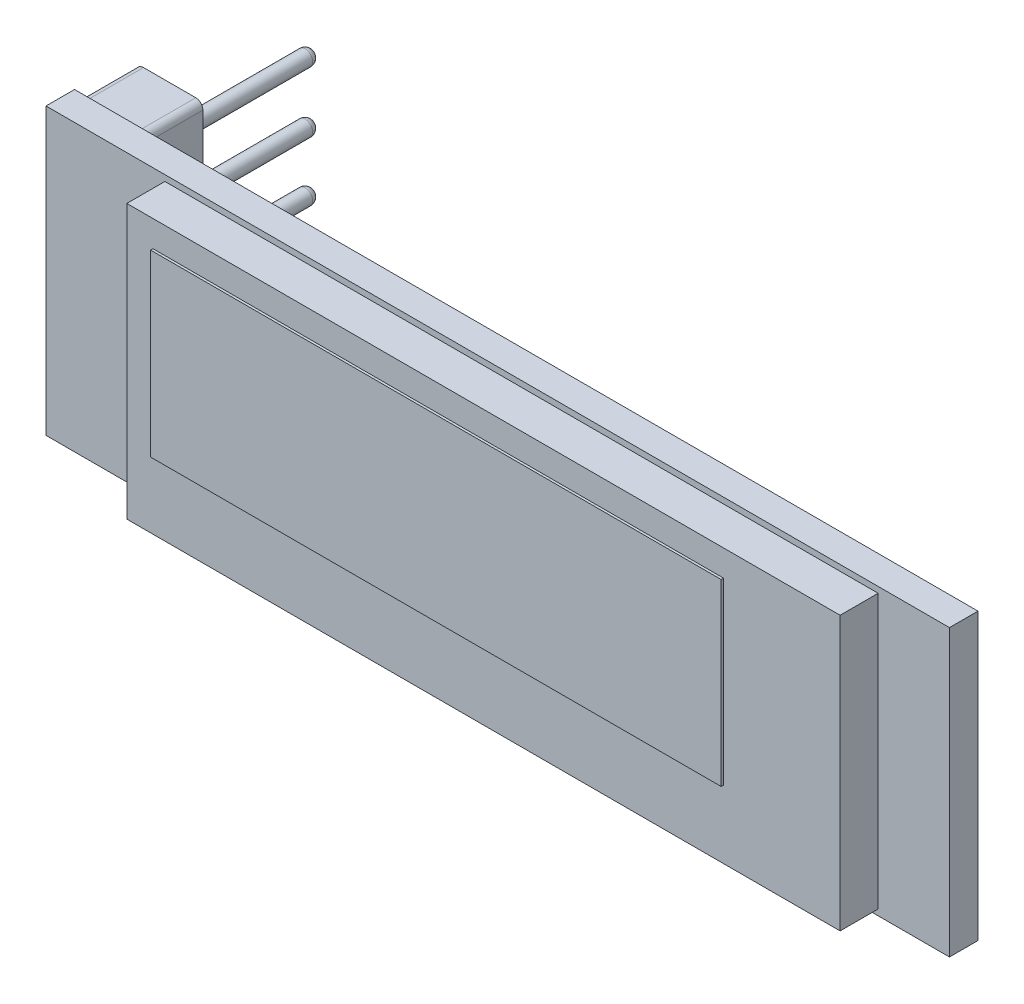
SolidWorks part; units mm, degrees
ref_plane "Front Plane" through (0, 0, 0) normal (0, 0, 1) x (1, 0, 0)
ref_plane "Top Plane" through (0, 0, 0) normal (0, 1, 0) x (1, 0, 0)
ref_plane "Right Plane" through (0, 0, 0) normal (1, 0, 0) x (0, 0, -1)
sketch "Sketch1" plane through (0, 0, 0) normal (0, 0, 1) x (1, 0, 0)
  line L1 (19, -6) -> (-19, -6)
  line L2 (19, -6) -> (19, 6)
  line L3 (19, 6) -> (-19, 6)
  line L4 (-19, -6) -> (-19, 6)
  line L5 (19, -6) -> (-19, 6) construction
  line L6 (19, 6) -> (-19, -6) construction
  point P0 (0, 0)
  dimension "D1" = 38
  dimension "D2" = 12
extrude "Boss-Extrude1" add sketch "Sketch1" along normal blind 1.2
sketch "Sketch2" plane through (0, 0, 1.2) normal (0, 0, 1) x (1, 0, 0)
  line L0 (-19, 6) -> (-19, -6) construction
  line L1 (-14, -5.75) -> (16, -5.75)
  line L2 (-14, -5.75) -> (-14, 5.75)
  line L3 (-14, 5.75) -> (16, 5.75)
  line L4 (16, -5.75) -> (16, 5.75)
  line L5 (-14, -5.75) -> (16, 5.75) construction
  line L6 (-14, 5.75) -> (16, -5.75) construction
  line L7 (-19, 0) -> (19, 0) construction
  line L8 (19, -6) -> (19, 6) construction
  point P0 (1, 0)
  dimension "D1" = 5
  dimension "D2" = 11.5
  dimension "D3" = 30
extrude "Boss-Extrude2" add sketch "Sketch2" along normal blind 1.6
sketch "Sketch4" plane through (0, 0, 2.8) normal (0, 0, 1) x (1, 0, 0)
  line L0 (-14, 0) -> (16, 0) construction
  line L1 (-14, 5.75) -> (-14, -5.75) construction
  line L2 (16, -5.75) -> (16, 5.75) construction
  line L3 (-19, 6) -> (-19, -6) construction
  line L4 (-12.9, 4.65) -> (11.1, 4.65)
  line L5 (-12.9, 4.65) -> (-12.9, -2.89)
  line L6 (-12.9, -2.89) -> (11.1, -2.89)
  line L7 (11.1, 4.65) -> (11.1, -2.89)
  line L8 (-12.9, 4.65) -> (11.1, -2.89) construction
  line L9 (-12.9, -2.89) -> (11.1, 4.65) construction
  line L10 (16, 5.75) -> (-14, 5.75) construction
  point P6 (-0.9, 0.88)
  dimension "D1" = 7.54
  dimension "D2" = 24
  dimension "D3" = 6.1
  dimension "D4" = 1.1
sketch "Sketch5" plane through (0, 0, 0) normal (0, 0, -1) x (-1, 0, 0)
  line L0 (17.5, 6) -> (17.5, -6) construction
  line L1 (-19, 6) -> (19, 6) construction
  line L2 (19, -6) -> (-19, -6) construction
  line L3 (19, 6) -> (19, -6) construction
  circle A0 centre (17.5, 3.81) radius 0.32
  circle A1 centre (17.5, 1.25) radius 0.32
  circle A2 centre (17.5, -1.25) radius 0.32
  circle A3 centre (17.5, -3.81) radius 0.32
  dimension "D2" = 0.64
  dimension "D1" = 1.5
  dimension "D3" = 7.62
  dimension "D4" = 2.56
  dimension "D5" = 2.56
  dimension "D6" = 2.19
sketch "Sketch6" plane through (0, 0, 0) normal (0, 0, -1) x (-1, 0, 0)
  line L0 (17.5, 6) -> (17.5, -6) construction
  line L1 (18.9, -5.75) -> (16.1, -5.75)
  line L2 (18.9, -5.75) -> (18.9, 5.75)
  line L3 (18.9, 5.75) -> (16.1, 5.75)
  line L4 (16.1, -5.75) -> (16.1, 5.75)
  line L5 (18.9, -5.75) -> (16.1, 5.75) construction
  line L6 (18.9, 5.75) -> (16.1, -5.75) construction
  point P0 (17.5, 0)
  dimension "D1" = 2.8
  dimension "D2" = 11.5
extrude "Boss-Extrude4" add sketch "Sketch6" along normal blind 2.5
extrude "Boss-Extrude5" add sketch "Sketch5" along normal blind 8.5
fillet "Fillet1" radius 0.3 4 edges at (-17.82, -3.81, -8.5) (-17.82, -1.25, -8.5) (-17.82, 1.25, -8.5) (-17.82, 3.81, -8.5)
fillet "Fillet2" radius 0.3 4 edges at (-16.1, 5.75, -1.25) (-18.9, 5.75, -1.25) (-16.1, -5.75, -1.25) (-18.9, -5.75, -1.25)
extrude "Boss-Extrude6" add sketch "Sketch4" along normal blind 0.1
